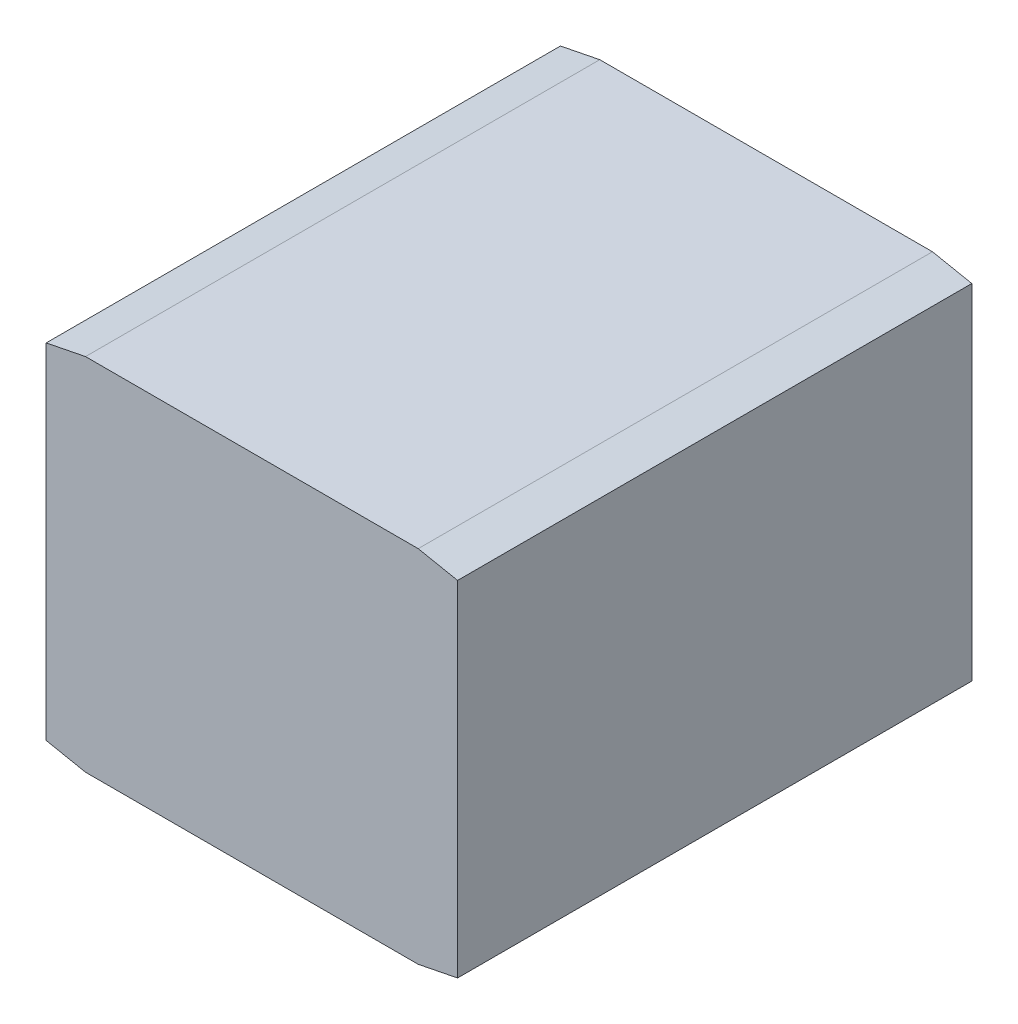
SolidWorks part; units mm, degrees
ref_plane "Plan de face" through (0, 0, 0) normal (0, 0, 1) x (1, 0, 0)
ref_plane "Plan de dessus" through (0, 0, 0) normal (0, 1, 0) x (1, 0, 0)
ref_plane "Plan de droite" through (0, 0, 0) normal (1, 0, 0) x (0, 0, -1)
sketch "Esquisse1" plane through (0, 0, 0) normal (0, 0, 1) x (1, 0, 0)
  line L0 (4, 3.3478) -> (3.2346, 3.5)
  line L1 (-3.2346, -3.5) -> (3.2346, -3.5)
  line L2 (-4, -3.3478) -> (-4, 3.3478)
  line L3 (-3.2346, 3.5) -> (3.2346, 3.5)
  line L4 (4, -3.3478) -> (4, 3.3478)
  line L5 (-4, -3.5) -> (4, 3.5) construction
  line L6 (-4, 3.5) -> (4, -3.5) construction
  line L7 (0, -3.5) -> (0, 7.7802) construction
  line L8 (-5.2625, 0) -> (8.5, 0) construction
  line L9 (-4, 3.3478) -> (-3.2346, 3.5)
  line L10 (4, -3.3478) -> (3.2346, -3.5)
  line L11 (-4, -3.3478) -> (-3.2346, -3.5)
  point P0 (0, 0)
  dimension "D1" = 7
  dimension "D2" = 8
  dimension "D3" = 11.25
extrude "Boss.-Extru.1" add sketch "Esquisse1" along normal blind 10
